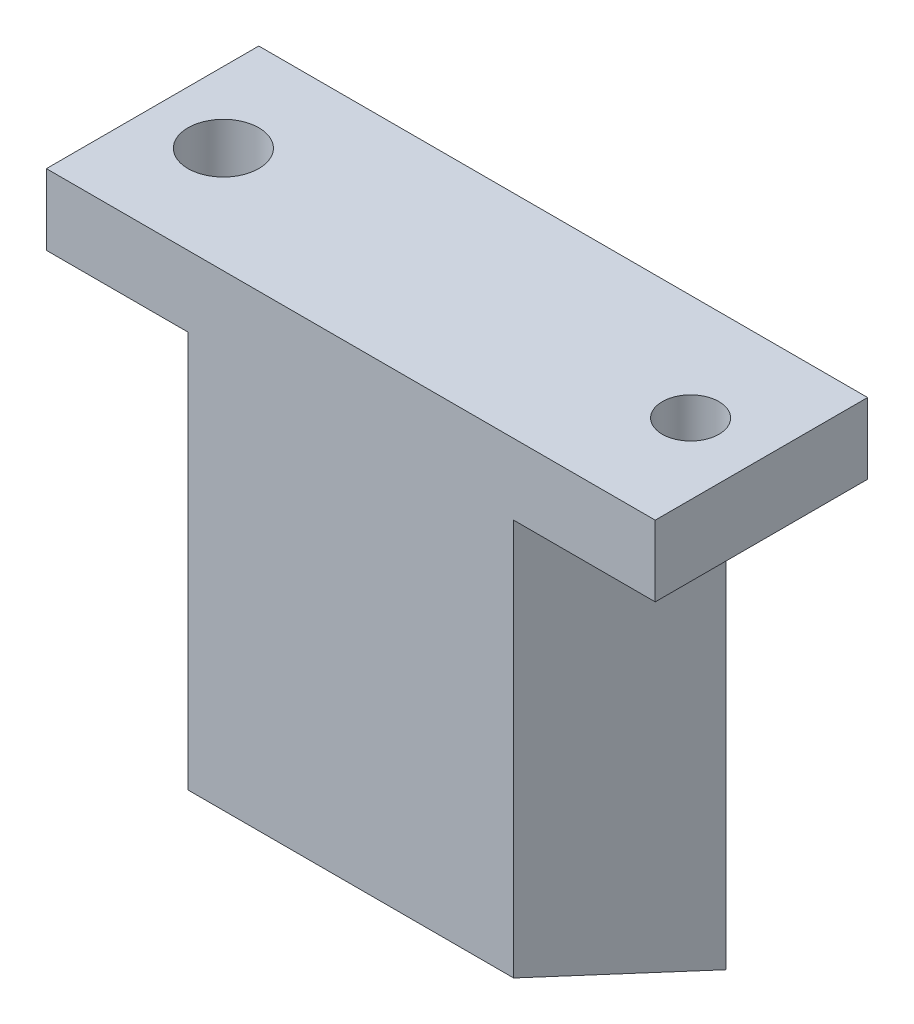
SolidWorks part; units mm, degrees
material "ABS"
ref_plane "Front Plane" through (0, 0, 0) normal (0, 0, 1) x (1, 0, 0)
ref_plane "Top Plane" through (0, 0, 0) normal (0, 1, 0) x (1, 0, 0)
ref_plane "Right Plane" through (0, 0, 0) normal (1, 0, 0) x (0, 0, -1)
sketch "Sketch1" plane through (0, 0, 0) normal (0, 1, 0) x (1, 0, 0)
  line L1 (-76.9048, 16.0714) -> (-53.9048, 16.0714)
  line L2 (-76.9048, 16.0714) -> (-76.9048, 1.0714)
  line L3 (-76.9048, 1.0714) -> (-53.9048, 1.0714)
  line L4 (-53.9048, 16.0714) -> (-53.9048, 1.0714)
  dimension "D1" = 15
  dimension "D2" = 23
extrude "Boss-Extrude1" add sketch "Sketch1" along normal blind 40
sketch "Sketch2" plane through (-53.9048, 0, 0) normal (1, 0, 0) x (0, 0, -1)
  line L3 (1.0714, 0) -> (16.0714, 0) construction
  line L5 (16.0714, 0) -> (1.0714, 0)
  line L6 (16.0714, 40) -> (16.0714, 0) construction
  line L7 (1.0714, 40) -> (1.0714, 0) construction
  line L8 (1.0714, 0) -> (1.0714, 6.9946)
  line L9 (1.0714, 6.9946) -> (16.0714, 0)
  dimension "D1" = 25
  dimension "D2" = 0
extrude "Cut-Extrude1" cut sketch "Sketch2" against normal blind 40
sketch "Sketch3" plane through (0, 6.1557, -2.8705) normal (0, -0.9063, 0.4226) x (1, 0, 0)
  line L0 (-76.9048, 1.985) -> (-53.9048, 1.985) construction
  line L2 (-53.9048, -14.5657) -> (-53.9048, 1.985) construction
  circle A0 centre (-65.3786, -5.515) radius 1.5
  point P4 (-65.4048, 1.985)
  point P7 (-53.9048, -6.2903)
  dimension "D1" = 7.5
  dimension "D2" = 11.5
  dimension "D3" = 3
extrude "Cut-Extrude2" cut sketch "Sketch3" against normal blind 36
sketch "Sketch4" plane through (-53.9048, 0, 0) normal (1, 0, 0) x (0, 0, -1)
  line L0 (1.0714, 40) -> (1.0714, 6.9946) construction
  line L1 (16.0714, 40) -> (1.0714, 40)
  line L2 (16.0714, 40) -> (16.0714, 35)
  line L3 (16.0714, 35) -> (1.0714, 35)
  line L4 (1.0714, 40) -> (1.0714, 35)
  dimension "D1" = 5
extrude "Boss-Extrude2" add sketch "Sketch4" along normal blind 10
sketch "Sketch5" plane through (-76.9048, 0, 0) normal (-1, 0, 0) x (0, 0, 1)
  line L0 (-1.0714, 40) -> (-1.0714, 6.9946) construction
  line L1 (-16.0714, 40) -> (-1.0714, 40)
  line L2 (-16.0714, 40) -> (-16.0714, 35)
  line L3 (-16.0714, 35) -> (-1.0714, 35)
  line L4 (-1.0714, 40) -> (-1.0714, 35)
  dimension "D1" = 5
extrude "Boss-Extrude3" add sketch "Sketch5" along normal blind 10
sketch "Sketch6" plane through (0, 35, 0) normal (0, -1, 0) x (1, 0, 0)
  line L0 (-86.9048, -16.0714) -> (-86.9048, -1.0714) construction
  line L1 (-86.9048, -1.0714) -> (-76.9048, -1.0714) construction
  line L2 (-43.9048, -1.0714) -> (-43.9048, -16.0714) construction
  circle A0 centre (-81.9048, -8.5714) radius 2.5
  circle A1 centre (-48.9048, -8.5714) radius 2
  dimension "D1" = 5
  dimension "D2" = 7.5
  dimension "D3" = 0
  dimension "D4" = 5
  dimension "D5" = 4
  dimension "D6" = 5
extrude "Cut-Extrude3" cut sketch "Sketch6" against normal blind 10
